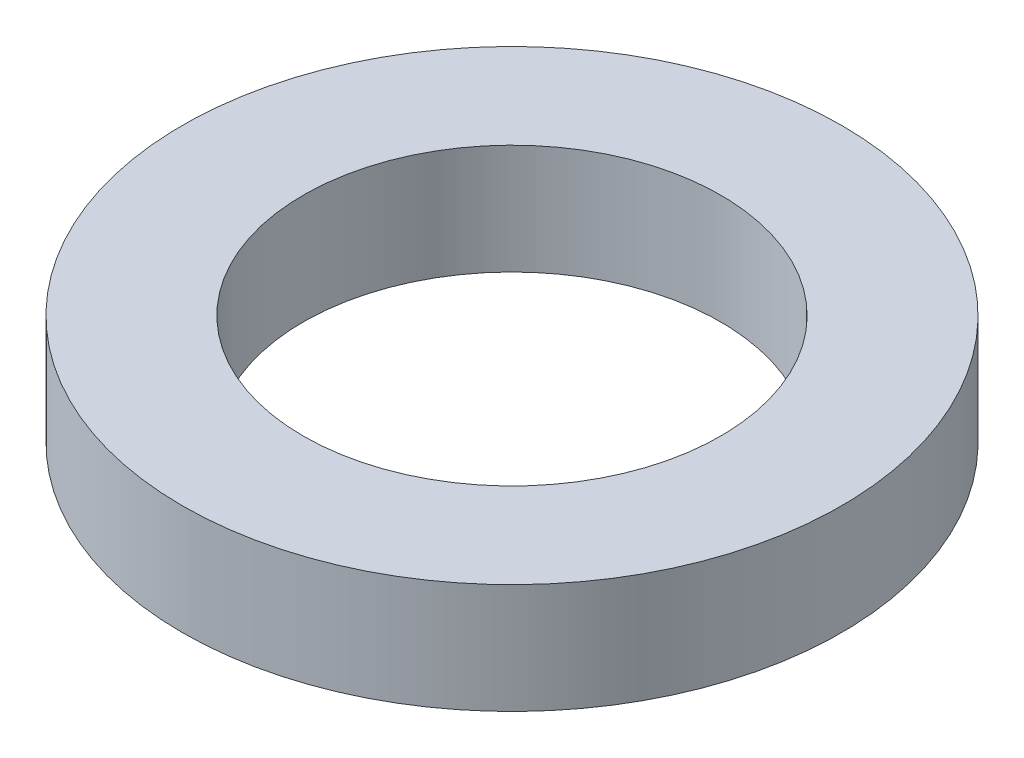
SolidWorks part; units mm, degrees
ref_plane "Front Plane" through (0, 0, 0) normal (0, 0, 1) x (1, 0, 0)
ref_plane "Top Plane" through (0, 0, 0) normal (0, 1, 0) x (1, 0, 0)
ref_plane "Right Plane" through (0, 0, 0) normal (1, 0, 0) x (0, 0, -1)
sketch "Sketch2" plane through (0, 0, 0) normal (0, 1, 0) x (1, 0, 0)
  circle A0 centre (0, 0) radius 3
  circle A1 centre (0, 0) radius 1.9
  dimension "D1" = 3.8
  dimension "D2" = 6
extrude "Boss-Extrude1" add sketch "Sketch2" along normal blind 1
